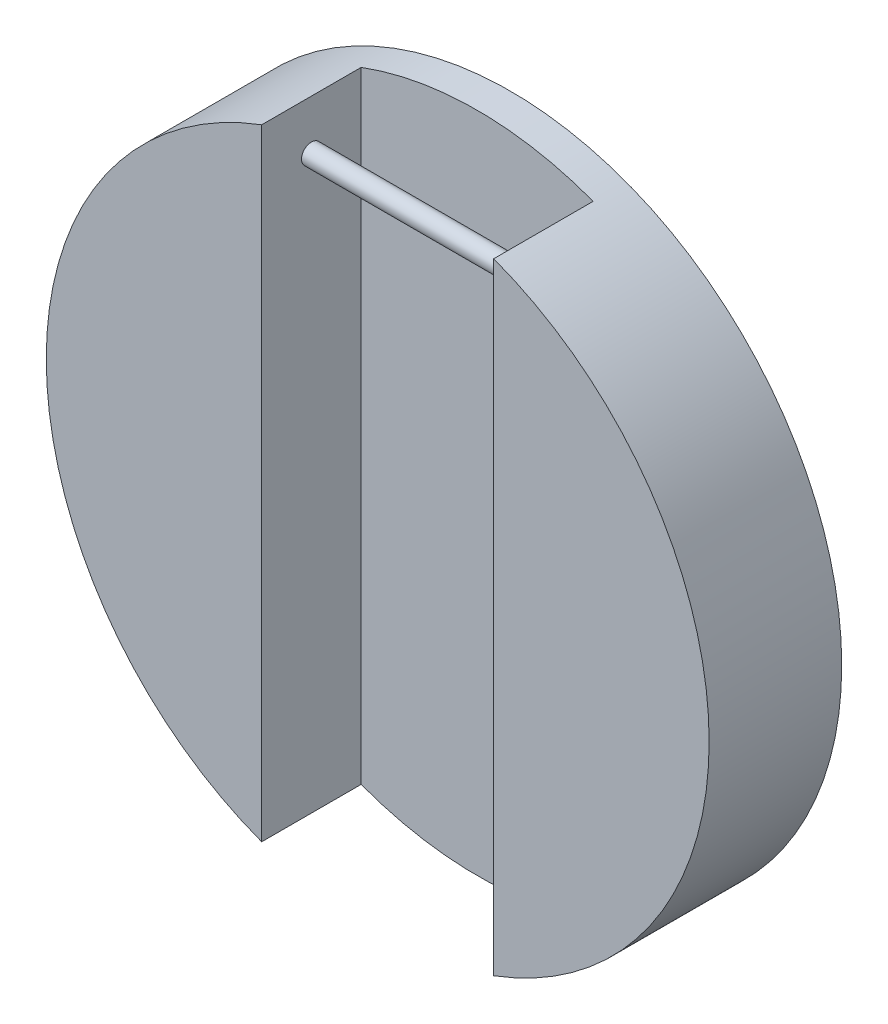
SolidWorks part; units mm, degrees
ref_plane "前视基准面" through (0, 0, 0) normal (0, 0, 1) x (1, 0, 0)
ref_plane "上视基准面" through (0, 0, 0) normal (0, 1, 0) x (1, 0, 0)
ref_plane "右视基准面" through (0, 0, 0) normal (1, 0, 0) x (0, 0, -1)
sketch "草图2" plane through (0, 0, 0) normal (0, 0, 1) x (1, 0, 0)
  circle A0 centre (0, 0) radius 100
  dimension "D1" = 200
extrude "凸台-拉伸1" add sketch "草图2" along normal blind 40
sketch "草图3" plane through (0, 0, 40) normal (0, 0, 1) x (1, 0, 0)
  line L0 (0, 100) -> (0, -100) construction
  line L1 (0, -100) -> (35, -100)
  line L2 (35, -100) -> (35, 100)
  line L3 (35, 100) -> (-35, 100)
  line L4 (-35, 100) -> (-35, -100)
  line L5 (-35, -100) -> (0, -100)
  circle A0 centre (0, 0) radius 100 construction
  dimension "D1" = 35
  dimension "D2" = 70
extrude "切除-拉伸1" cut sketch "草图3" against normal blind 30
sketch "草图4" plane through (-35, 0, 0) normal (1, 0, 0) x (0, 0, -1)
  line L0 (-10, 93.675) -> (-10, 78.675) construction
  line L1 (-10, 93.675) -> (-10, -93.675) construction
  line L2 (-10, 78.675) -> (-25, 78.675) construction
  circle A0 centre (-25, 78.675) radius 3
  dimension "D1" = 15
  dimension "D2" = 15
extrude "凸台-拉伸2" add sketch "草图4" along normal blind 74
